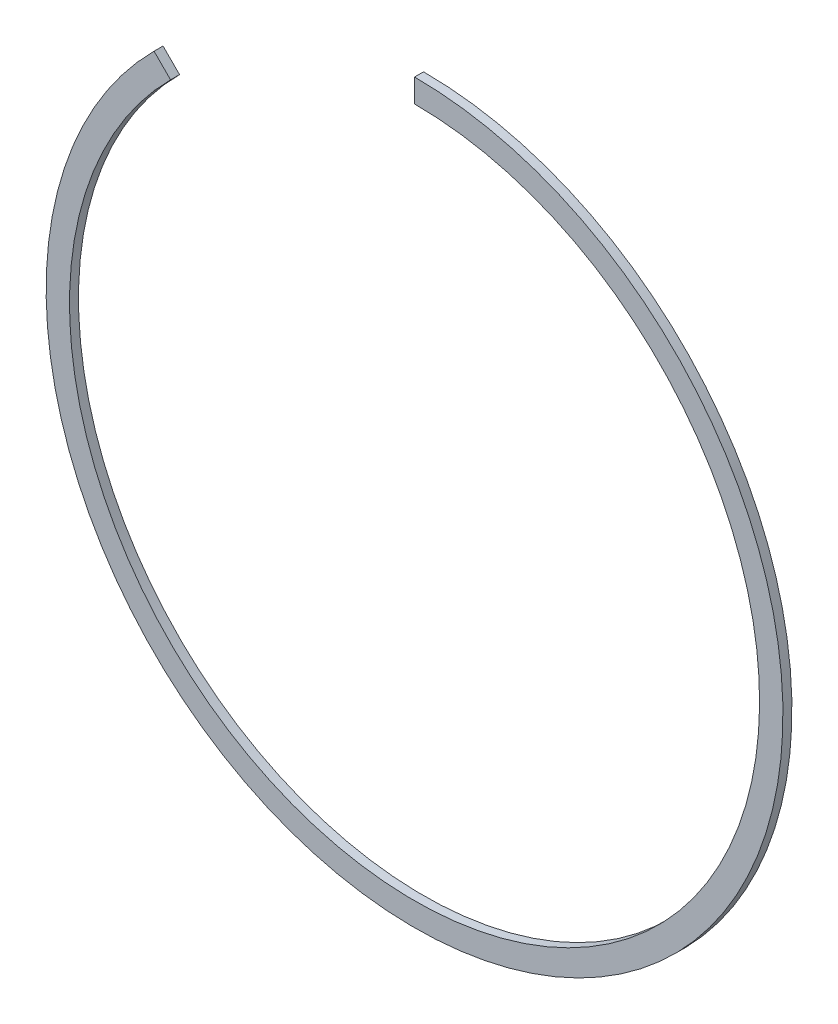
SolidWorks part; units mm, degrees
material "1.0503 (C45)"
ref_plane "Front Plane" through (0, 0, 0) normal (0, 0, 1) x (1, 0, 0)
ref_plane "Top Plane" through (0, 0, 0) normal (0, 1, 0) x (1, 0, 0)
ref_plane "Right Plane" through (0, 0, 0) normal (1, 0, 0) x (0, 0, -1)
sketch "Sketch1" plane through (0, 0, 0) normal (0, 0, 1) x (1, 0, 0)
  line L0 (0, 96) -> (0, 102.5)
  line L1 (0, 0) -> (0, 146.833) construction
  line L2 (0, 0) -> (-72.4784, 72.4784) construction
  line L3 (-72.4784, 72.4784) -> (-67.8823, 67.8823)
  circle A0 centre (0, 0) radius 102.5
  circle A1 centre (0, 0) radius 96
  dimension "D1" = 205
  dimension "D2" = 192
extrude "Boss-Extrude1" add sketch "Sketch1" along normal blind 2.5 contours A1 L3 A0 L0
